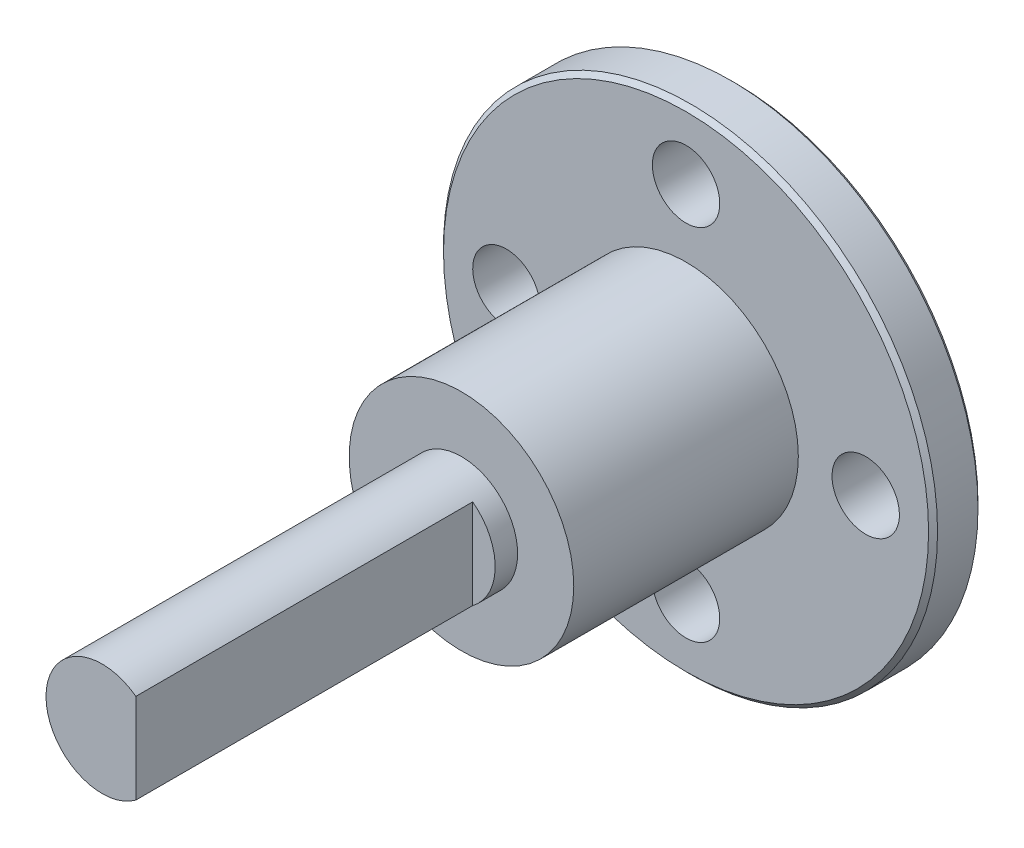
SolidWorks part; units mm, degrees
material "AISI 304"
ref_plane "前视基准面" through (0, 0, 0) normal (0, 0, 1) x (1, 0, 0)
ref_plane "上视基准面" through (0, 0, 0) normal (0, 1, 0) x (1, 0, 0)
ref_plane "右视基准面" through (0, 0, 0) normal (1, 0, 0) x (0, 0, -1)
sketch "草图1" plane through (0, 0, 0) normal (0, 0, 1) x (1, 0, 0)
  circle A3 centre (0, 0) radius 5
  circle A4 centre (0, 0) radius 11
  point P7 (0, 0)
  dimension "D1" = 22
  dimension "D2" = 10
extrude "凸台-拉伸1" add sketch "草图1" along normal blind 2.2 contours A3 | A4 A3
sketch "草图2" plane through (0, 0, 2.2) normal (0, 0, 1) x (1, 0, 0)
  circle A0 centre (0, 0) radius 5
  dimension "D1" = 10
extrude "凸台-拉伸2" add sketch "草图2" along normal blind 10
hole_wizard "Ø3.0mm 暗销孔1" positions "草图8" profile "草图9" hole size "Ø3.0" standard "GB" end condition through all
sketch "草图8" plane through (0, 0, 2.2) normal (0, 0, 1) x (1, 0, 0)
  line L0 (0, 0) -> (0, 8) construction
  point P0 (0, 8)
  dimension "D1" = 8
sketch "草图9" plane through (0, 8, 2.2) normal (1, 0, 0) x (0, -1, 0)
  line L0 (0, 0) -> (0, 2.2)
  line L1 (0, 2.2) -> (1.5, 2.2)
  line L2 (1.5, 2.2) -> (1.5, 0)
  line L5 (1.5, 0) -> (0, 0)
  line L11 (0, -6.35) -> (0, 107.95) construction
  dimension "通孔孔直径" = 3
  dimension "通孔孔深度" = 2.2
pattern_circular "阵列(圆周)1" count 4 over 360 about axis through (0, 0, 0) along (0, 0, 1) of "Ø3.0mm 暗销孔1"
chamfer "倒角3" distance 0.2 angle 45 2 edges at (11, 0, 2.2) (11, 0, 0)
sketch "草图12" plane through (0, 0, 2.2) normal (0, 0, 1) x (1, 0, 0)
  circle A0 centre (0, 0) radius 2.5
  dimension "D1" = 5
extrude "轴" add sketch "草图12" along normal blind 26
sketch "草图13" plane through (0, 0, 28.2) normal (0, 0, 1) x (1, 0, 0)
  line L0 (0, 0) -> (4.1196, 0) construction
  line L1 (1.5, 2.6158) -> (1.5, -2.6158)
  circle A0 centre (0, 0) radius 2.5 construction
  circle A1 centre (0, 0) radius 2.5
  point P6 (1.5, 0)
  circle M2 centre (0, 0) radius 2.5
  dimension "D1" = 1.5
extrude "切除-拉伸1" cut sketch "草图13" against normal blind 15 contours L0 L1 M2 | L1 L0 A1
